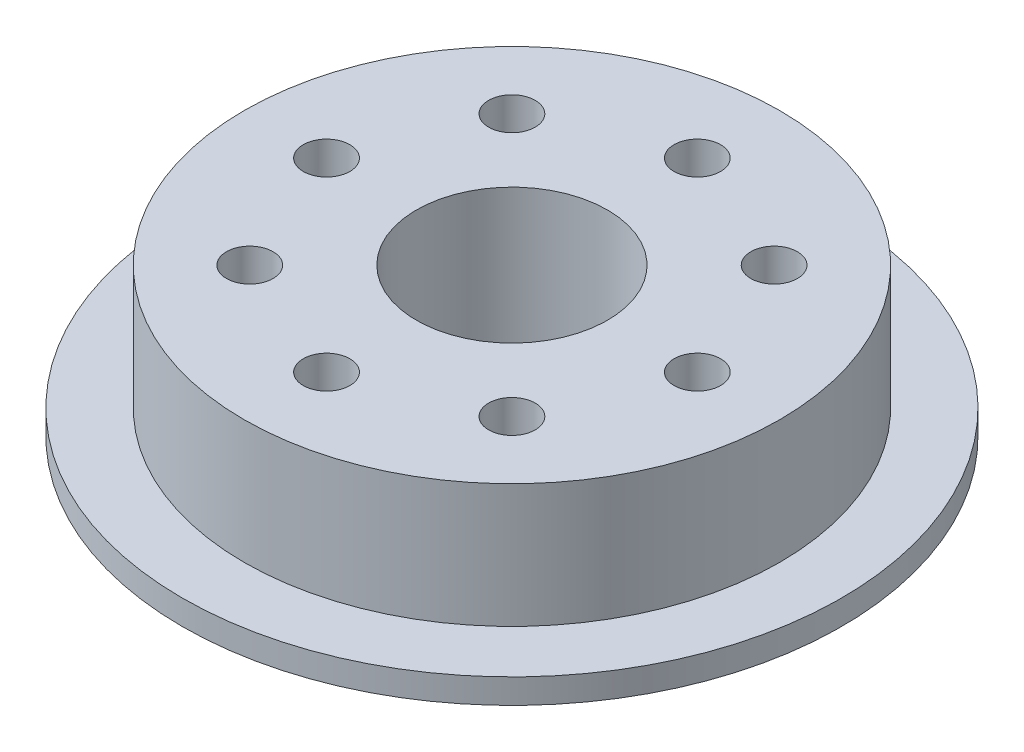
SolidWorks part; units mm, degrees
ref_plane "Front Plane" through (0, 0, 0) normal (0, 0, 1) x (1, 0, 0)
ref_plane "Top Plane" through (0, 0, 0) normal (0, 1, 0) x (1, 0, 0)
ref_plane "Right Plane" through (0, 0, 0) normal (1, 0, 0) x (0, 0, -1)
sketch "Sketch1" plane through (0, 0, 0) normal (0, 1, 0) x (1, 0, 0)
  circle A0 centre (0, 0) radius 40
  dimension "D1" = 80
extrude "Boss-Extrude1" add sketch "Sketch1" along normal blind 3
sketch "Sketch3" plane through (0, 3, 0) normal (0, 1, 0) x (1, 0, 0)
  circle A0 centre (0, 0) radius 32.5
  dimension "D1" = 65
extrude "Boss-Extrude2" add sketch "Sketch3" along normal blind 15
sketch "Sketch4" plane through (0, 18, 0) normal (0, 1, 0) x (1, 0, 0)
  line L0 (0, -1.65) -> (0, 1.65) construction
  circle A0 centre (0, 22.5) radius 2.8253
  circle A1 centre (15.9099, 15.9099) radius 2.8253
  circle A2 centre (22.5, 0) radius 2.8253
  circle A3 centre (15.9099, -15.9099) radius 2.8253
  circle A4 centre (0, -22.5) radius 2.8253
  circle A5 centre (-15.9099, -15.9099) radius 2.8253
  circle A6 centre (-22.5, 0) radius 2.8253
  circle A7 centre (-15.9099, 15.9099) radius 2.8253
  point P21 (0, 0)
  dimension "D1" = 22.5
  dimension "D2" = 8
extrude "Cut-Extrude1" cut sketch "Sketch4" against normal through all
sketch "Sketch5" plane through (0, 0, 0) normal (0, -1, 0) x (1, 0, 0)
  circle A0 centre (0, 0) radius 11.6
  dimension "D1" = 23.2
extrude "Cut-Extrude2" cut sketch "Sketch5" against normal through all
